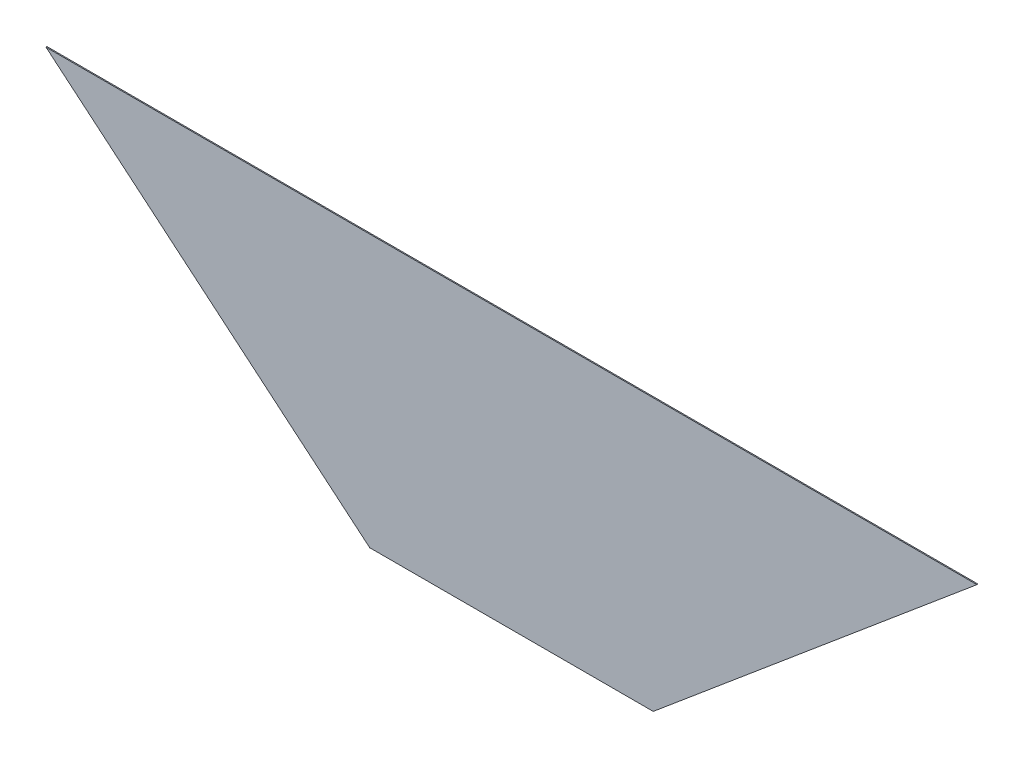
SolidWorks part; units mm, degrees
ref_plane "Alzado" through (0, 0, 0) normal (0, 0, 1) x (1, 0, 0)
ref_plane "Planta" through (0, 0, 0) normal (0, 1, 0) x (1, 0, 0)
ref_plane "Vista lateral" through (0, 0, 0) normal (1, 0, 0) x (0, 0, -1)
sketch "Croquis1" plane through (0, 0, 0) normal (0, 0, 1) x (1, 0, 0)
  line L0 (0, 0) -> (790.88, 0)
  line L1 (0, 0) -> (-903.1228, 757.81)
  line L2 (790.88, 0) -> (1694.0028, 757.81)
  line L3 (395.44, 0) -> (395.44, 757.81) construction
  line L4 (395.44, 757.81) -> (1694.0028, 757.81)
  line L5 (395.44, 757.81) -> (-903.1228, 757.81)
  dimension "D1" = 790.88
  dimension "D2" = 140
  dimension "D3" = 140
  dimension "D4" = 757.81
extrude "Saliente-Extruir1" add sketch "Croquis1" along normal blind 2.9
